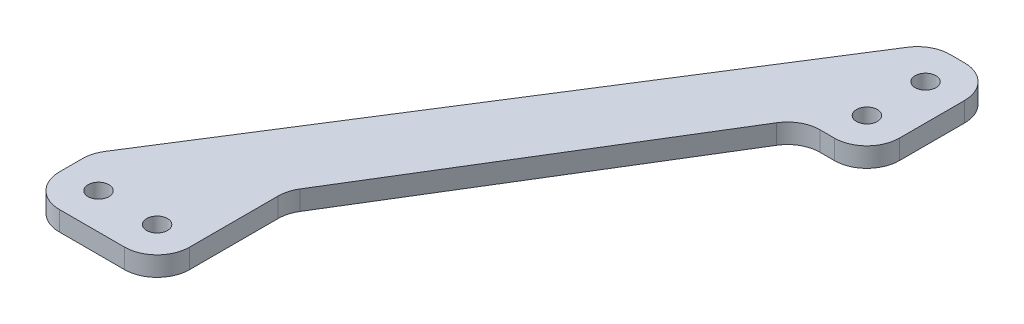
SolidWorks part; units mm, degrees
material "6061-T6 (SS)"
ref_plane "前视基准面" through (0, 0, 0) normal (0, 0, 1) x (1, 0, 0)
ref_plane "上视基准面" through (0, 0, 0) normal (0, 1, 0) x (1, 0, 0)
ref_plane "右视基准面" through (0, 0, 0) normal (1, 0, 0) x (0, 0, -1)
sketch "草图1" plane through (0, 0, 0) normal (0, 1, 0) x (1, 0, 0)
  line L0 (50, 89) -> (0, 10)
  line L1 (0, 0) -> (60, 0) construction
  line L2 (0, 0) -> (0, 89) construction
  line L3 (0, 89) -> (60, 89) construction
  line L4 (60, 0) -> (60, 89) construction
  line L5 (30, 89) -> (30, 0) construction
  line L6 (0, 44.5) -> (60, 44.5) construction
  line L7 (60, 89) -> (40, 89) construction
  line L8 (60, 89) -> (60, 69) construction
  line L9 (60, 69) -> (40, 69) construction
  line L10 (40, 89) -> (40, 69) construction
  line L11 (50, 69) -> (50, 89) construction
  line L12 (60, 79) -> (40, 79) construction
  line L13 (45.5, 83.5) -> (54.5, 83.5) construction
  line L14 (45.5, 83.5) -> (45.5, 74.5) construction
  line L15 (45.5, 74.5) -> (54.5, 74.5) construction
  line L16 (54.5, 83.5) -> (54.5, 74.5) construction
  line L17 (50, 74.5) -> (50, 83.5) construction
  line L18 (45.5, 79) -> (54.5, 79) construction
  line L19 (0, 0) -> (20, 0) construction
  line L20 (0, 0) -> (0, 20) construction
  line L21 (0, 20) -> (20, 20) construction
  line L22 (20, 0) -> (20, 20) construction
  line L23 (10, 20) -> (10, 0) construction
  line L24 (0, 10) -> (20, 10) construction
  line L25 (14.5, 14.5) -> (5.5, 14.5) construction
  line L26 (14.5, 14.5) -> (14.5, 5.5) construction
  line L27 (14.5, 5.5) -> (5.5, 5.5) construction
  line L28 (5.5, 14.5) -> (5.5, 5.5) construction
  line L29 (10, 5.5) -> (10, 14.5) construction
  line L30 (14.5, 10) -> (5.5, 10) construction
  line L31 (0, 10) -> (0, 0)
  line L32 (0, 0) -> (20, 0)
  line L34 (60, 69) -> (60, 89)
  line L35 (60, 89) -> (50, 89)
  line L36 (60, 69) -> (50, 69)
  line L37 (50, 69) -> (20, 20)
  line L38 (20, 20) -> (20, 0)
  circle A0 centre (54.5, 83.5) radius 1.6
  circle A1 centre (54.5, 74.5) radius 1.6
  circle A2 centre (5.5, 5.5) radius 1.6
  circle A3 centre (14.5, 5.5) radius 1.6
  point P7 (50, 79)
  point P16 (10, 10)
  point P23 (0, 0.2026)
  point P149 (10, 10)
  point P164 (30, 44.5)
  point P173 (50, 79)
  dimension "D7" = 20
  dimension "D1" = 60
  dimension "D2" = 89
  dimension "D3" = 20
  dimension "D4" = 20
  dimension "D5" = 9
  dimension "D6" = 9
  dimension "D8" = 20
  dimension "D9" = 9
  dimension "D10" = 9
extrude "凸台-拉伸1" add sketch "草图1" along normal blind 3
fillet "圆角1" radius 5 8 edges at (0, 1.5, -10) (50, 1.5, -89) (60, 1.5, -89) (60, 1.5, -69) (50, 1.5, -69) (0, 1.5, 0) (20, 1.5, -20) (20, 1.5, 0)
